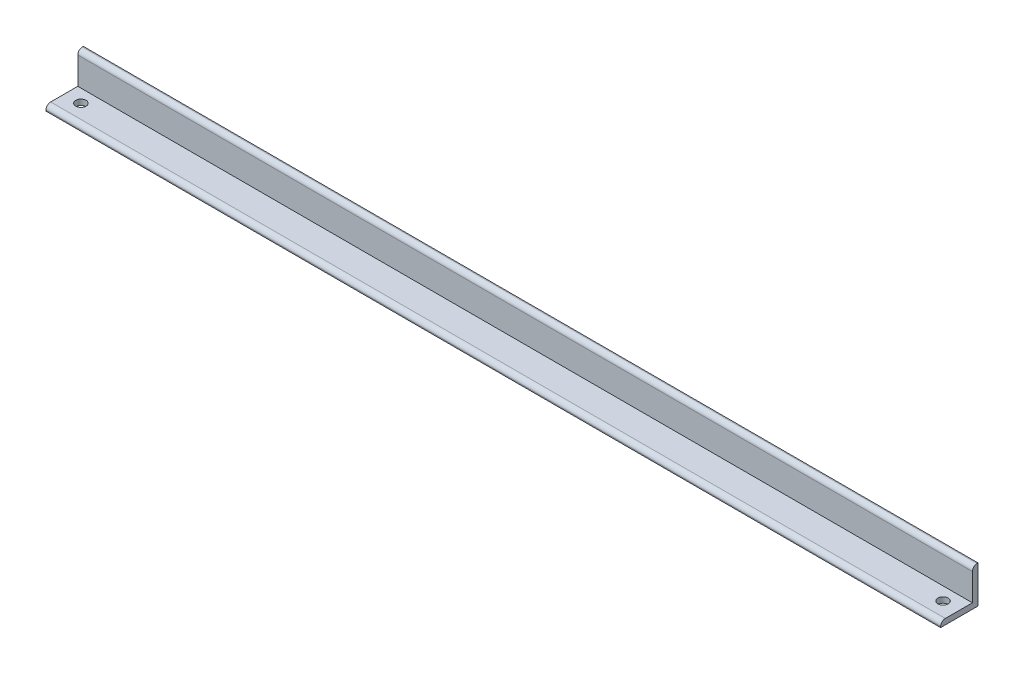
SolidWorks part; units mm, degrees
ref_plane "前视基准面" through (0, 0, 0) normal (0, 0, 1) x (1, 0, 0)
ref_plane "上视基准面" through (0, 0, 0) normal (0, 1, 0) x (1, 0, 0)
ref_plane "右视基准面" through (0, 0, 0) normal (1, 0, 0) x (0, 0, -1)
sketch "草图1" plane through (0, 0, 0) normal (0, 0, 1) x (1, 0, 0)
  line L1 (0, 0) -> (1915, 0)
  line L2 (0, 0) -> (0, 80)
  line L3 (0, 80) -> (1915, 80)
  line L4 (1915, 0) -> (1915, 80)
  dimension "D1" = 1915
  dimension "D2" = 80
extrude "拉伸1" add sketch "草图1" along normal blind 80
sketch "草图3" plane through (0, 0, 0) normal (-1, 0, 0) x (0, 0, 1)
  line L0 (80, 80) -> (80, 0) construction
  line L1 (12, 80) -> (80, 80)
  line L2 (12, 80) -> (12, 12)
  line L3 (12, 12) -> (80, 12)
  line L4 (80, 80) -> (80, 12)
  line L5 (80, 80) -> (0, 80) construction
  line L6 (80, 0) -> (0, 0) construction
  line L7 (0, 80) -> (0, 0) construction
  dimension "D1" = 12
  dimension "D2" = 12
extrude "拉伸2" cut sketch "草图3" against normal through all
fillet "圆角1" radius 10 2 edges at (957.5, 12, 80) (957.5, 80, 12)
sketch "草图7" plane through (0, 0, 0) normal (0, -1, 0) x (1, 0, 0)
  line L0 (0, 0) -> (1915, 0) construction
  line L1 (0, 80) -> (0, 0) construction
  circle A0 centre (34.75, 40) radius 11
  dimension "D1" = 40
  dimension "D3" = 22
  dimension "D2" = 34.75
extrude "拉伸5" cut sketch "草图7" against normal through all
pattern_linear "阵列(线性)3" count 2 spacing 1845.3834 along (1, 0, 0) of "拉伸5"
